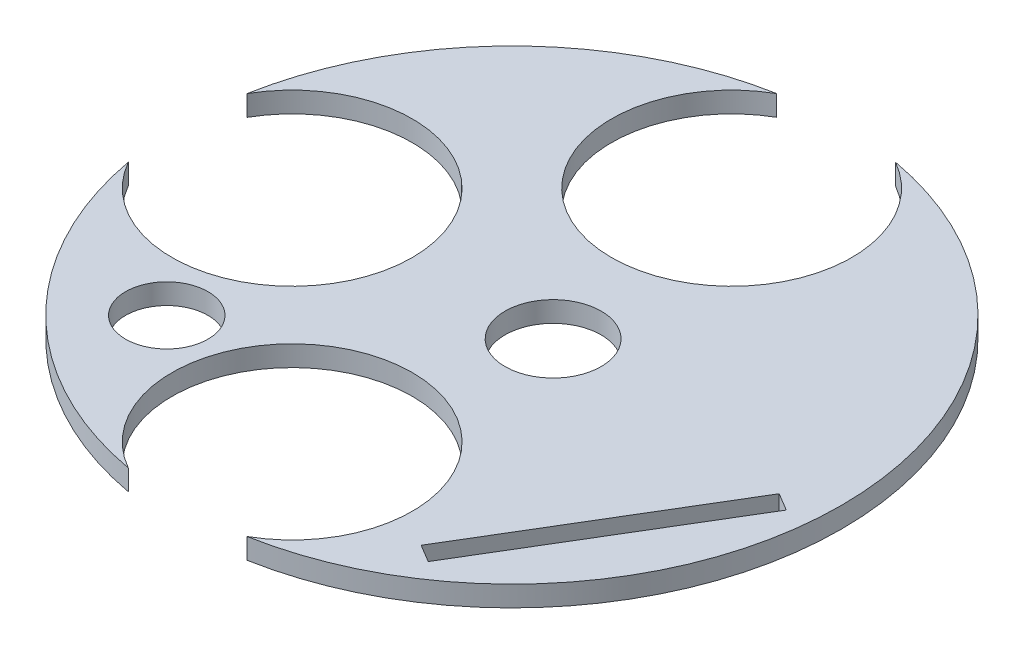
SolidWorks part; units mm, degrees
material "Acrylique (impact moyen-haut)"
ref_plane "Plan de face" through (0, 0, 0) normal (0, 0, 1) x (1, 0, 0)
ref_plane "Plan de dessus" through (0, 0, 0) normal (0, 1, 0) x (1, 0, 0)
ref_plane "Plan de droite" through (0, 0, 0) normal (1, 0, 0) x (0, 0, -1)
sketch "Esquisse1" plane through (0, 0, 0) normal (0, 1, 0) x (1, 0, 0)
  line L0 (0, 0) -> (3, 0) construction
  line L5 (3, 0) -> (-12.5429, -12.5864) construction
  line L6 (-16, 0) -> (0, 0) construction
  line L7 (21, -1.5351) -> (11.2143, -17.8212)
  line L8 (11.2143, -17.8212) -> (12.5, -18.5938)
  line L9 (12.5, -18.5938) -> (22.2858, -2.3076)
  line L10 (22.2858, -2.3076) -> (21, -1.5351)
  circle A0 centre (0, 0) radius 24
  circle A4 centre (-12.5429, -12.5864) radius 3
  circle A5 centre (0, 0) radius 16 construction
  circle A7 centre (3, 0) radius 3.5
  circle A8 centre (0, 0) radius 18.7911 construction
  circle A10 centre (-16, 0) radius 8.75
  circle A11 centre (0, 16) radius 8.75
  circle A12 centre (0, -16) radius 8.75
  point P16 (16.1071, -9.6781)
  dimension "D1" = 48
  dimension "D5" = 6
  dimension "D6" = 32
  dimension "D7" = 7
  dimension "D13" = 17.5
  dimension "D8" = 3
  dimension "D9" = 20
  dimension "D10" = 19
  dimension "D11" = 39
  dimension "D12" = 1.5
  dimension "D14" = 20
  dimension "D15" = 18
extrude "Boss.-Extru.1" add sketch "Esquisse1" along normal blind 1.5 contours A12 A0 A11 A10 A7 A4 L10 L9 L8 L7
